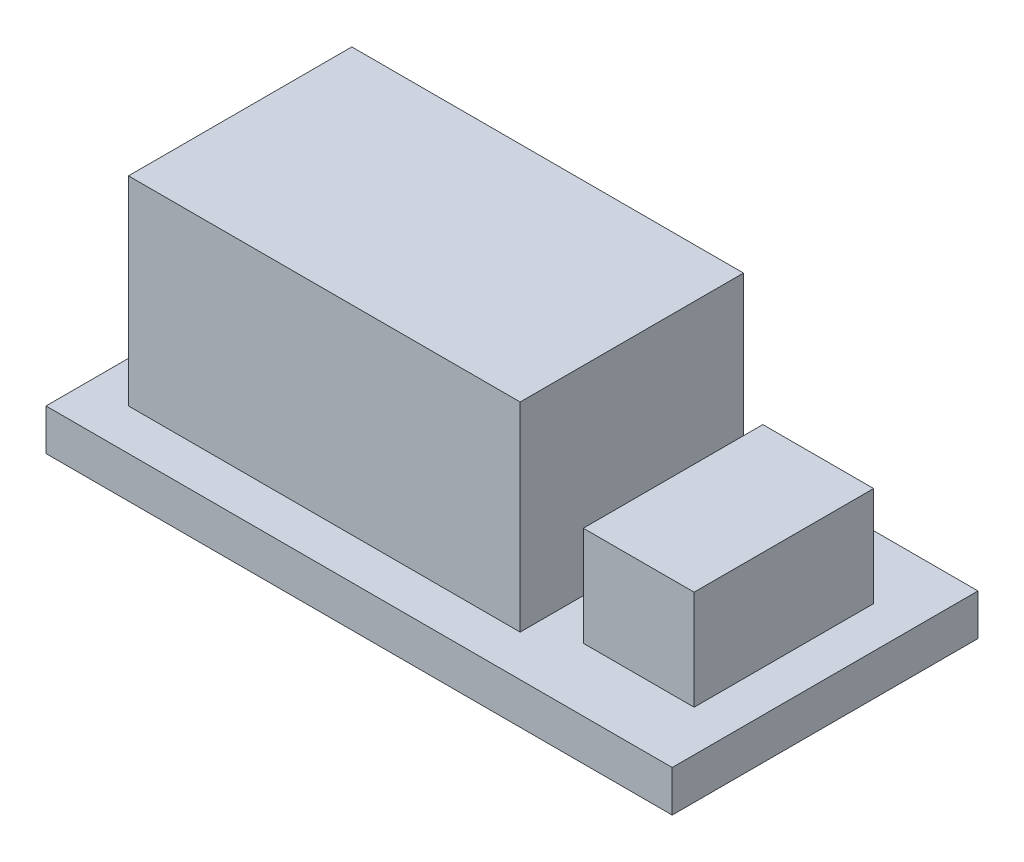
SolidWorks part; units mm, degrees
ref_plane "Front" through (0, 0, 0) normal (0, 0, 1) x (1, 0, 0)
ref_plane "Top" through (0, 0, 0) normal (0, 1, 0) x (1, 0, 0)
ref_plane "Right" through (0, 0, 0) normal (1, 0, 0) x (0, 0, -1)
sketch "Sketch1" plane through (0, 0, 0) normal (0, 1, 0) x (1, 0, 0)
  line L1 (-1447.8, 825.5) -> (1447.8, 825.5)
  line L2 (-1447.8, 825.5) -> (-1447.8, -825.5)
  line L3 (-1447.8, -825.5) -> (1447.8, -825.5)
  line L4 (1447.8, 825.5) -> (1447.8, -825.5)
  line L5 (-1447.8, 825.5) -> (1447.8, -825.5) construction
  line L6 (-1447.8, -825.5) -> (1447.8, 825.5) construction
  point P0 (0, 0)
  dimension "D1" = 2895.6
  dimension "D2" = 1651
extrude "Boss-Extrude1" add sketch "Sketch1" along normal blind 1473.2
sketch "Sketch2" plane through (0, 0, 0) normal (0, -1, 0) x (1, 0, 0)
  line L0 (0, 0) -> (2162.175, 0) construction
  line L1 (1447.8, 825.5) -> (1447.8, -825.5) construction
  line L2 (1752.6, 663.575) -> (2571.75, 663.575)
  line L3 (1752.6, 663.575) -> (1752.6, -663.575)
  line L4 (1752.6, -663.575) -> (2571.75, -663.575)
  line L5 (2571.75, 663.575) -> (2571.75, -663.575)
  line L6 (1752.6, 663.575) -> (2571.75, -663.575) construction
  line L7 (1752.6, -663.575) -> (2571.75, 663.575) construction
  dimension "D1" = 1327.15
  dimension "D2" = 819.15
  dimension "D3" = 304.8
extrude "Boss-Extrude2" add sketch "Sketch2" against normal blind 736.6 separate body
sketch "Sketch3" plane through (0, 0, 0) normal (0, -1, 0) x (1, 0, 0)
  line L0 (0, 0) -> (561.975, 0) construction
  line L1 (2571.75, -663.575) -> (2571.75, 663.575) construction
  line L2 (-1752.6, 1130.3) -> (2876.55, 1130.3)
  line L3 (-1752.6, 1130.3) -> (-1752.6, -1130.3)
  line L4 (-1752.6, -1130.3) -> (2876.55, -1130.3)
  line L5 (2876.55, 1130.3) -> (2876.55, -1130.3)
  line L6 (-1752.6, 1130.3) -> (2876.55, -1130.3) construction
  line L7 (-1752.6, -1130.3) -> (2876.55, 1130.3) construction
  line L8 (-1447.8, 825.5) -> (1447.8, 825.5) construction
  line L9 (-1447.8, -825.5) -> (-1447.8, 825.5) construction
  dimension "D1" = 304.8
  dimension "D2" = 304.8
  dimension "D3" = 304.8
  dimension "D4" = 2260.6
  dimension "D5" = 4629.15
extrude "Boss-Extrude3" add sketch "Sketch3" along normal blind 304.8 separate body
